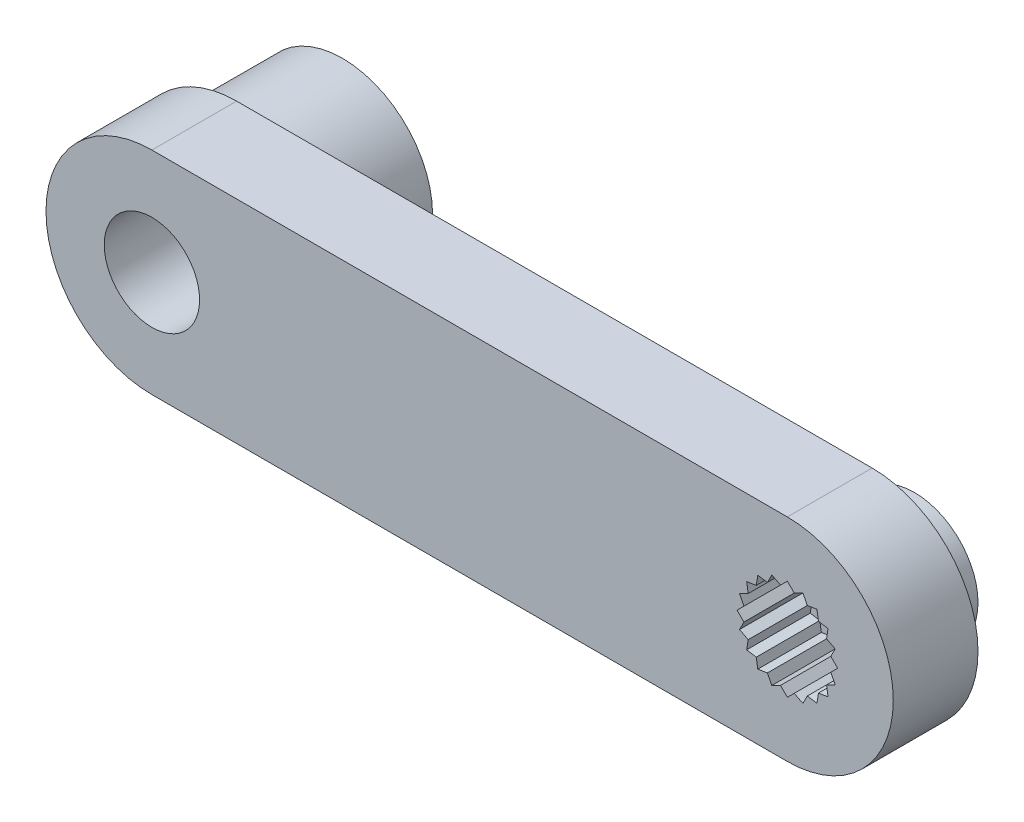
SolidWorks part; units mm, degrees
material "PET"
ref_plane "Front Plane" through (0, 0, 0) normal (0, 0, 1) x (1, 0, 0)
ref_plane "Top Plane" through (0, 0, 0) normal (0, 1, 0) x (1, 0, 0)
ref_plane "Right Plane" through (0, 0, 0) normal (1, 0, 0) x (0, 0, -1)
sketch "Sketch1" plane through (0, 0, 0) normal (0, 0, 1) x (1, 0, 0)
  line L0 (0, 0) -> (30, 0) construction
  line L1 (0, 5) -> (30, 5)
  line L2 (0, -5) -> (30, -5)
  arc A0 (0, 5) -> (0, -5) centre (0, 0) ccw
  arc A1 (30, -5) -> (30, 5) centre (30, 0) ccw
  circle A2 centre (0, 0) radius 2.25
  circle A4 centre (30, 0) radius 1
  point P3 (15, 0)
  dimension "D1" = 5
  dimension "D3" = 4.5
  dimension "D4" = 2
  dimension "D2" = 30
extrude "Boss-Extrude1" add sketch "Sketch1" along normal mid plane 4
sketch "Sketch3" plane through (0, 0, -2) normal (0, 0, -1) x (-1, 0, 0)
  circle A2 centre (-30, 0) radius 3
  circle A4 centre (-30, 0) radius 1 construction
  circle A5 centre (-30, 0) radius 1
  dimension "D1" = 6
extrude "Boss-Extrude2" add sketch "Sketch3" along normal blind 2
sketch "Sketch4" plane through (0, 0, -2) normal (0, 0, -1) x (-1, 0, 0)
  circle A0 centre (0, 0) radius 2.25 construction
  circle A1 centre (0, 0) radius 2.25
  circle A2 centre (0, 0) radius 4.25
  dimension "D1" = 2
extrude "Boss-Extrude3" add sketch "Sketch4" along normal blind 5
sketch "Sketch6" plane through (0, 0, 2) normal (0, 0, 1) x (1, 0, 0)
  line L0 (30, 2.0758) -> (30, 2.375) construction
  line L1 (29.6753, 2.0503) -> (30, 2.375)
  line L2 (30.3247, 2.0503) -> (30, 2.375)
  line L3 (30.3247, 2.0503) -> (30.7339, 2.2588)
  line L4 (30.9424, 1.8496) -> (30.7339, 2.2588)
  line L5 (30.9424, 1.8496) -> (31.396, 1.9214)
  line L6 (31.4678, 1.4678) -> (31.396, 1.9214)
  line L7 (31.4678, 1.4678) -> (31.9214, 1.396)
  line L8 (31.8496, 0.9424) -> (31.9214, 1.396)
  line L9 (31.8496, 0.9424) -> (32.2588, 0.7339)
  line L10 (32.0503, 0.3247) -> (32.2588, 0.7339)
  line L11 (32.0503, 0.3247) -> (32.375, 0)
  line L12 (32.0503, -0.3247) -> (32.375, 0)
  line L13 (32.0503, -0.3247) -> (32.2588, -0.7339)
  line L14 (31.8496, -0.9424) -> (32.2588, -0.7339)
  line L15 (31.8496, -0.9424) -> (31.9214, -1.396)
  line L16 (31.4678, -1.4678) -> (31.9214, -1.396)
  line L17 (31.4678, -1.4678) -> (31.396, -1.9214)
  line L18 (30.9424, -1.8496) -> (31.396, -1.9214)
  line L19 (30.9424, -1.8496) -> (30.7339, -2.2588)
  line L20 (30.3247, -2.0503) -> (30.7339, -2.2588)
  line L21 (30.3247, -2.0503) -> (30, -2.375)
  line L22 (29.6753, -2.0503) -> (30, -2.375)
  line L23 (29.6753, -2.0503) -> (29.2661, -2.2588)
  line L24 (29.0576, -1.8496) -> (29.2661, -2.2588)
  line L25 (29.0576, -1.8496) -> (28.604, -1.9214)
  line L26 (28.5322, -1.4678) -> (28.604, -1.9214)
  line L27 (28.5322, -1.4678) -> (28.0786, -1.396)
  line L28 (28.1504, -0.9424) -> (28.0786, -1.396)
  line L29 (28.1504, -0.9424) -> (27.7412, -0.7339)
  line L30 (27.9497, -0.3247) -> (27.7412, -0.7339)
  line L31 (27.9497, -0.3247) -> (27.625, 0)
  line L32 (27.9497, 0.3247) -> (27.625, 0)
  line L33 (27.9497, 0.3247) -> (27.7412, 0.7339)
  line L34 (28.1504, 0.9424) -> (27.7412, 0.7339)
  line L35 (28.1504, 0.9424) -> (28.0786, 1.396)
  line L36 (28.5322, 1.4678) -> (28.0786, 1.396)
  line L37 (28.5322, 1.4678) -> (28.604, 1.9214)
  line L38 (29.0576, 1.8496) -> (28.604, 1.9214)
  line L39 (29.0576, 1.8496) -> (29.2661, 2.2588)
  line L40 (29.6753, 2.0503) -> (29.2661, 2.2588)
  circle A0 centre (30, 0) radius 2.375 construction
  circle A1 centre (30, 0) radius 2.0758 construction
  circle A3 centre (30, 0) radius 1 construction
  point P67 (30, 0)
  dimension "D1" = 20
  dimension "D2" = 4.75
  dimension "D3" = 45
extrude "Cut-Extrude1" cut sketch "Sketch6" against normal blind 3
